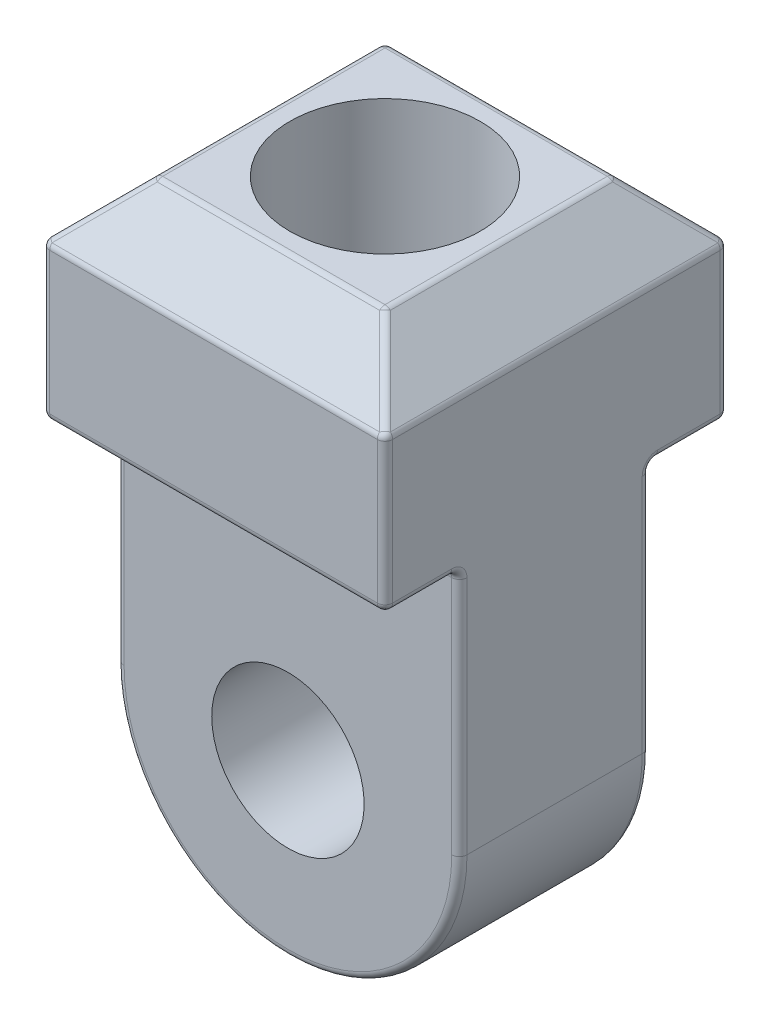
SolidWorks part; units mm, degrees
ref_plane "Front Plane" through (0, 0, 0) normal (0, 0, 1) x (1, 0, 0)
ref_plane "Top Plane" through (0, 0, 0) normal (0, 1, 0) x (1, 0, 0)
ref_plane "Right Plane" through (0, 0, 0) normal (1, 0, 0) x (0, 0, -1)
sketch "Sketch1" plane through (0, 0, 0) normal (0, 0, 1) x (1, 0, 0)
  line L0 (0, 0) -> (0, 25.222) construction
  line L1 (-4.5, 0) -> (-4.5, 10.5)
  line L2 (4.5, 0) -> (4.5, 10.5)
  line L3 (-3, 12) -> (3, 12)
  line L4 (-4.5, 10.5) -> (-3, 12)
  line L5 (3, 12) -> (4.5, 10.5)
  arc A0 (-4.5, 0) -> (4.5, 0) centre (0, 0) ccw
  circle A1 centre (0, 0) radius 2
  point P3 (0, 12.611)
  point P7 (4.5, 12)
  point P8 (-4.5, 12)
  point P12 (0, 12)
  dimension "D1" = 4
  dimension "D2" = 4.5
  dimension "D3" = 3
  dimension "D4" = 10.5
  dimension "D5" = 12.611
extrude "Boss-Extrude1" add sketch "Sketch1" along normal mid plane 9
sketch "Sketch2" plane through (0, 0, 0) normal (1, 0, 0) x (0, 0, -1)
  line L0 (2.4523, 6.5) -> (4.5, 6.5)
  line L2 (-2.5477, 6.5) -> (-2.5477, -4.5)
  line L4 (-4.5, -4.5) -> (4.5, -4.5) construction
  line L6 (2.4523, -4.5) -> (2.4523, 6.5)
  line L8 (4.5, 6.5) -> (4.5, -4.5)
  line L9 (4.5, -4.5) -> (4.5, 0) construction
  line L10 (4.5, -4.5) -> (2.4523, -4.5)
  line L11 (-4.5, -4.5) -> (-4.5, 6.5)
  line L12 (-2.5477, -4.5) -> (-4.5, -4.5)
  line L14 (-4.5, 6.5) -> (-2.5477, 6.5)
  dimension "D1" = 2.4523
  dimension "D2" = 2.5477
  dimension "D3" = 6.5
extrude "Cut-Extrude1" cut sketch "Sketch2" against normal through all both and the other way through all
sketch "Sketch3" plane through (0, 0, 0) normal (1, 0, 0) x (0, 0, -1)
  line L0 (-3, 12) -> (-4.5, 10.5)
  line L5 (3, 12) -> (4.5, 10.5)
  line L6 (-4.5, 10.5) -> (-4.5, 12)
  line L7 (-4.5, 12) -> (-3, 12)
  line L8 (3, 12) -> (4.5, 12)
  line L9 (4.5, 12) -> (4.5, 10.5)
  point P0 (-4.5, 12)
  point P3 (4.5, 12)
  dimension "D1" = 3
  dimension "D2" = 4.5
extrude "Cut-Extrude2" cut sketch "Sketch3" against normal through all both and the other way through all
sketch "Sketch4" plane through (0, 12, 0) normal (0, 1, 0) x (1, 0, 0)
  circle A0 centre (0, 0) radius 2.5
  dimension "D1" = 5
extrude "Cut-Extrude3" cut sketch "Sketch4" against normal blind 5 and the other way through all
fillet "Fillet1" radius 0.2 30 edges at (0, -4.5, 2.5477) (4.5, 3.25, 2.5477) (-4.5, 3.25, 2.5477) (0, 6.5, 2.5477) (4.5, 6.5, 3.5239) (0, -4.5, -2.4523) (4.5, 3.25, -2.4523) (-4.5, 6.5, 3.5239) (0, 6.5, 4.5) (0, 12, 3) (3.75, 11.25, 3.75) (3, 12, 0) (4.5, 6.5, -3.4761) (-4.5, 3.25, -2.4523) (0, 6.5, -2.4523) (0, 10.5, 4.5) (-3.75, 11.25, 3.75) (-3, 12, 0) (0, 12, -3) (4.5, 10.5, 0) (3.75, 11.25, -3.75) (0, 6.5, -4.5) (-4.5, 6.5, -3.4761) (-4.5, 10.5, 0) (-3.75, 11.25, -3.75) (0, 10.5, -4.5) (-4.5, 8.5, -4.5) (-4.5, 8.5, 4.5) (4.5, 8.5, -4.5) (4.5, 8.5, 4.5)
